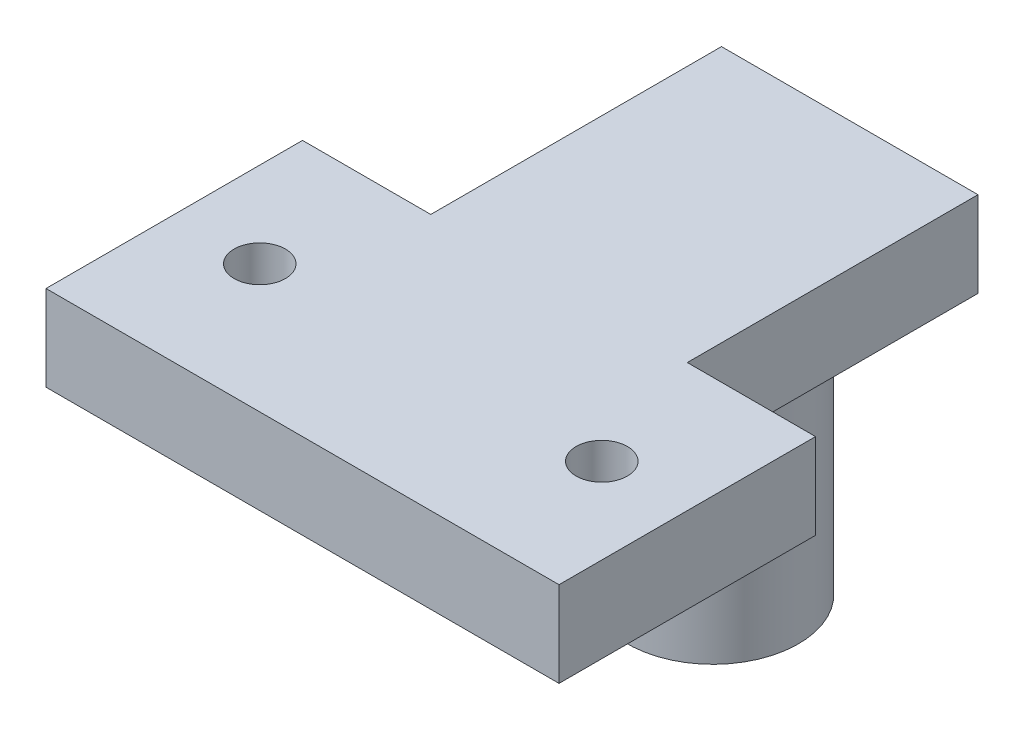
SolidWorks part; units mm, degrees
ref_plane "Front Plane" through (0, 0, 0) normal (0, 0, 1) x (1, 0, 0)
ref_plane "Top Plane" through (0, 0, 0) normal (0, 1, 0) x (1, 0, 0)
ref_plane "Right Plane" through (0, 0, 0) normal (1, 0, 0) x (0, 0, -1)
sketch "Sketch1" plane through (0, 0, 0) normal (0, 1, 0) x (1, 0, 0)
  line L0 (88.4146, -9.1695) -> (88.2301, -9.1695)
  line L1 (0, 0) -> (-30, 0)
  line L2 (0, 0) -> (0, -15)
  line L3 (0, -15) -> (-30, -15)
  line L4 (-30, 0) -> (-30, -15)
  line L5 (-19.2921, 9) -> (-10.2921, 9) construction
  line L6 (-22.5, 0) -> (-7.5, 0)
  line L7 (-22.5, 0) -> (-22.5, 17)
  line L8 (-22.5, 17) -> (-7.5, 17)
  line L9 (-7.5, 0) -> (-7.5, 17)
  line L10 (-15, 15.296) -> (-15, 7.9135) construction
  line L11 (-30, -7.5) -> (0, -7.5) construction
  line L12 (-25, -4.9457) -> (-25, -10.679) construction
  line L13 (-5, -4.9457) -> (-5, -10.679) construction
  circle A0 centre (-15, 9) radius 5
  circle A1 centre (-25, -7.5) radius 1.5
  circle A2 centre (-5, -7.5) radius 1.5
  point P11 (-15, 0)
  point P16 (-15, 11.6048)
  dimension "D8" = 10
  dimension "D11" = 3
  dimension "D12" = 3
  dimension "D13" = 5
  dimension "D1" = 15
  dimension "D2" = 30
  dimension "D3" = 15
  dimension "D4" = 7.5
  dimension "D5" = 17
  dimension "D6" = 9
  dimension "D7" = 7.5
  dimension "D9" = 5
  dimension "D10" = 5
extrude "Boss-Extrude1" add sketch "Sketch1" along normal blind 5 contours L1 L4 L3 L2 A2 A1 | L1 L9 L8 L7 A0 | A0
sketch "Sketch3" plane through (0, 0, 0) normal (0, -1, 0) x (1, 0, 0)
  line L0 (-7.5, 0) -> (-22.5, 0) construction
  line L1 (-15, 0) -> (-15, -14.4157) construction
  line L2 (-12.6145, -9) -> (-17.7019, -9) construction
  circle A0 centre (-15, -9) radius 5
  dimension "D2" = 10
  dimension "D1" = 9
extrude "Boss-Extrude2" add sketch "Sketch3" along normal blind 15
